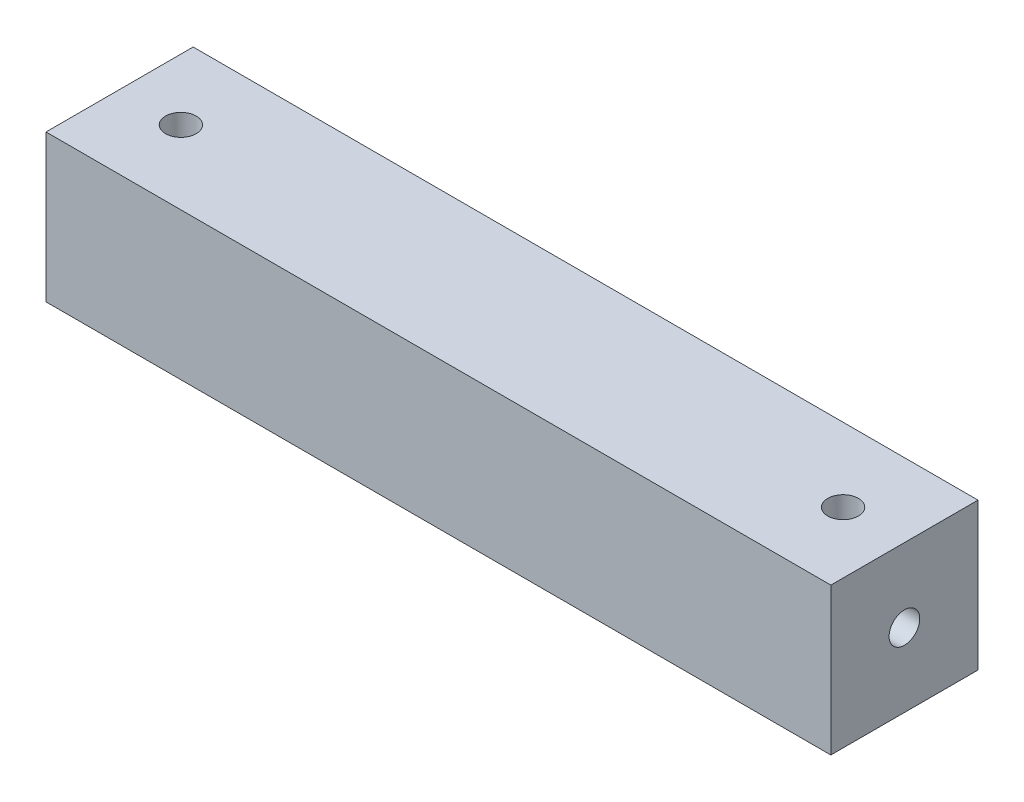
SolidWorks part; units mm, degrees
ref_plane "Plan de face" through (0, 0, 0) normal (0, 0, 1) x (1, 0, 0)
ref_plane "Plan de dessus" through (0, 0, 0) normal (0, 1, 0) x (1, 0, 0)
ref_plane "Plan de droite" through (0, 0, 0) normal (1, 0, 0) x (0, 0, -1)
sketch "Esquisse1" plane through (0, 0, 0) normal (0, 0, 1) x (1, 0, 0)
  line L5 (0, -6) -> (-32, -6)
  line L6 (0, -6) -> (0, 0)
  line L7 (0, 0) -> (-32, 0)
  line L8 (-32, -6) -> (-32, 0)
  point P4 (0, -2.8765)
  dimension "D1" = 32
  dimension "D2" = 6
extrude "Boss.-Extru.1" add sketch "Esquisse1" along normal blind 6
sketch "Esquisse2" plane through (-32, 0, 0) normal (-1, 0, 0) x (0, 0, 1)
  circle A0 centre (3, -3) radius 0.625
  point P2 (0, 0)
  point P5 (2.9092, -2.0206)
  dimension "D1" = 1.25
  dimension "D2" = 3
  dimension "D3" = 3
extrude "Enlèv. mat.-Extru.1" cut sketch "Esquisse2" against normal through all
sketch "Esquisse3" plane through (0, -6, 0) normal (0, -1, 0) x (1, 0, 0)
  line L0 (-32, 6) -> (-32, 0) construction
  line L1 (0, 6) -> (0, 0) construction
  circle A0 centre (-29.5, 3) radius 0.625
  circle A1 centre (-2.5, 3) radius 0.625
  dimension "D5" = 1.25
  dimension "D6" = 1.25
  dimension "D1" = 2.5
  dimension "D2" = 3
  dimension "D3" = 2.5
  dimension "D4" = 3
extrude "Enlèv. mat.-Extru.2" cut sketch "Esquisse3" against normal through all
